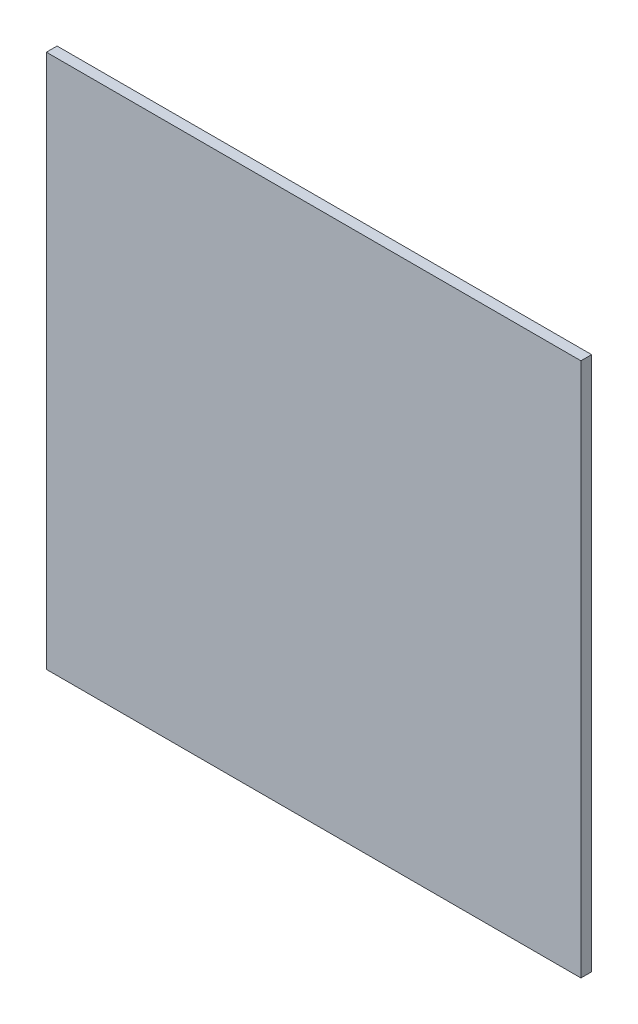
SolidWorks part; units mm, degrees
ref_plane "Front Plane" through (0, 0, 0) normal (0, 0, 1) x (1, 0, 0)
ref_plane "Top Plane" through (0, 0, 0) normal (0, 1, 0) x (1, 0, 0)
ref_plane "Right Plane" through (0, 0, 0) normal (1, 0, 0) x (0, 0, -1)
sketch "Sketch1" plane through (0, 0, 0) normal (0, 0, 1) x (1, 0, 0)
  line L1 (9.525, 9.525) -> (-9.525, 9.525)
  line L2 (9.525, 9.525) -> (9.525, -9.525)
  line L3 (9.525, -9.525) -> (-9.525, -9.525)
  line L4 (-9.525, 9.525) -> (-9.525, -9.525)
  line L5 (9.525, 9.525) -> (-9.525, -9.525) construction
  line L6 (9.525, -9.525) -> (-9.525, 9.525) construction
  point P0 (0, 0)
  dimension "D1" = 19.05
  dimension "D2" = 19.05
extrude "Boss-Extrude1" add sketch "Sketch1" along normal blind 0.381
